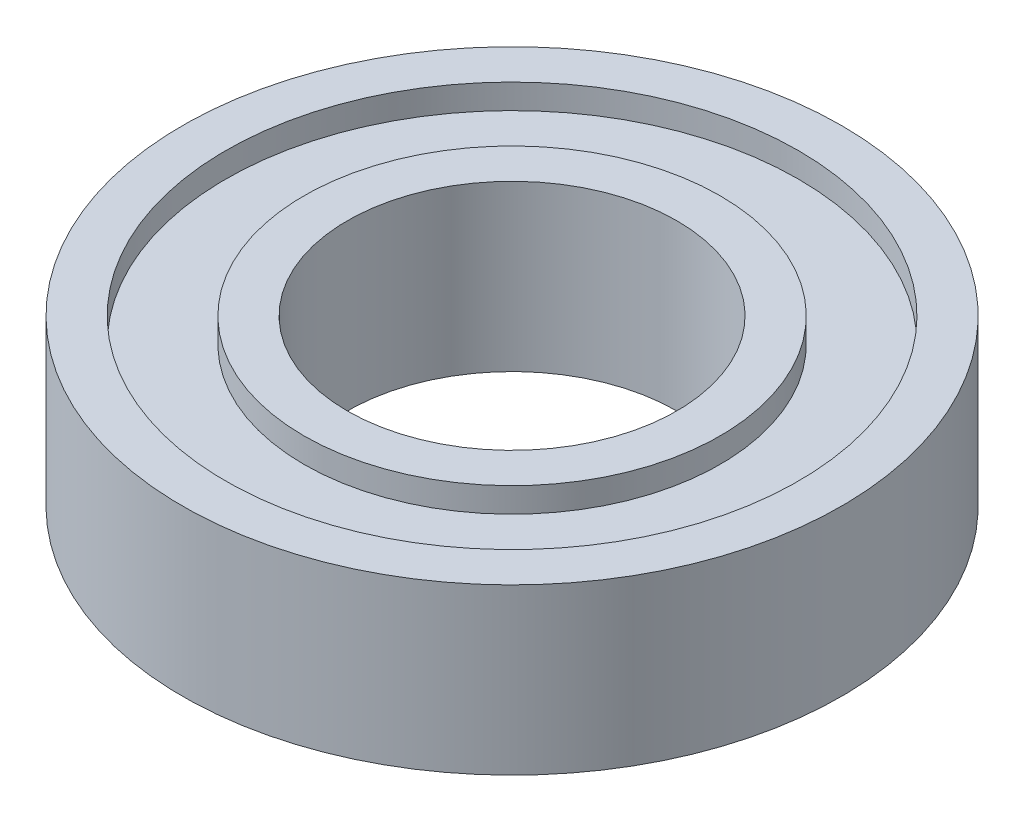
SolidWorks part; units mm, degrees
material "Cast Alloy Steel"
ref_plane "Front Plane" through (0, 0, 0) normal (0, 0, 1) x (1, 0, 0)
ref_plane "Top Plane" through (0, 0, 0) normal (0, 1, 0) x (1, 0, 0)
ref_plane "Right Plane" through (0, 0, 0) normal (1, 0, 0) x (0, 0, -1)
sketch "Sketch1" plane through (0, 0, 0) normal (0, 0, 1) x (1, 0, 0)
  line L0 (4, 0) -> (4, 4)
  line L1 (4, 4) -> (5.05, 4)
  line L2 (5.05, 4) -> (5.05, 3.4)
  line L3 (5.05, 3.4) -> (6.95, 3.4)
  line L4 (6.95, 3.4) -> (6.95, 4)
  line L5 (6.95, 4) -> (8, 4)
  line L6 (8, 4) -> (8, 0)
  line L7 (8, 0) -> (6.95, 0)
  line L8 (6.95, 0) -> (6.95, 0.6)
  line L9 (6.95, 0.6) -> (5.05, 0.6)
  line L10 (5.05, 0.6) -> (5.05, 0)
  line L11 (5.05, 0) -> (4, 0)
  line L12 (0, 0) -> (0, 5.903) construction
  dimension "D1" = 1.05
  dimension "D2" = 4
  dimension "D3" = 8
  dimension "D4" = 4
  dimension "D5" = 0.6
revolve "Revolve1" add sketch "Sketch1" angle 360 about L12
